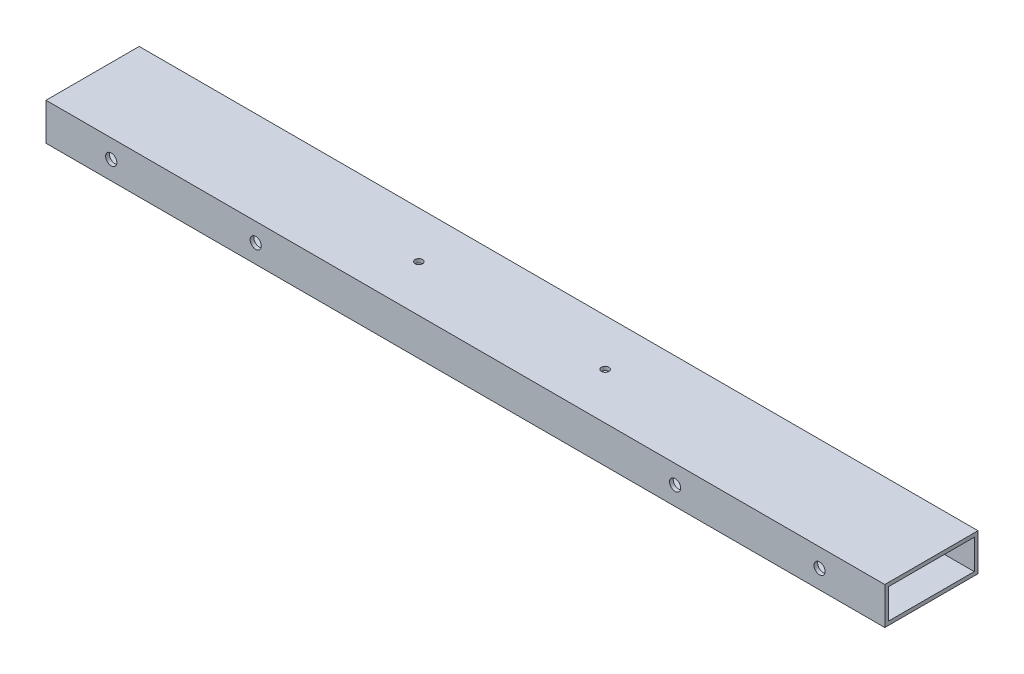
SolidWorks part; units mm, degrees
ref_plane "Спереди" through (0, 0, 0) normal (0, 0, 1) x (1, 0, 0)
ref_plane "Сверху" through (0, 0, 0) normal (0, 1, 0) x (1, 0, 0)
ref_plane "Справа" through (0, 0, 0) normal (1, 0, 0) x (0, 0, -1)
sketch "Эскиз1" plane through (0, 0, 0) normal (1, 0, 0) x (0, 0, -1)
  line L1 (-25, 10) -> (25, 10)
  line L2 (-25, 10) -> (-25, -10)
  line L3 (-25, -10) -> (25, -10)
  line L4 (25, 10) -> (25, -10)
  line L5 (-25, 10) -> (25, -10) construction
  line L6 (-25, -10) -> (25, 10) construction
  line L7 (-23, -8) -> (23, -8)
  line L8 (-23, -8) -> (-23, 8)
  line L9 (-23, 8) -> (23, 8)
  line L10 (23, -8) -> (23, 8)
  line L11 (-23, -8) -> (23, 8) construction
  line L12 (-23, 8) -> (23, -8) construction
  point P0 (0, 0)
  point P5 (0, 0)
  dimension "D1" = 46
  dimension "D2" = 16
  dimension "D3" = 50
  dimension "D4" = 20
extrude "Бобышка-Вытянуть1" add sketch "Эскиз1" along normal blind 450
sketch "Эскиз2" plane through (0, 0, -25) normal (0, 0, -1) x (-1, 0, 0)
  line L0 (-450, -10) -> (-450, 10) construction
  circle A0 centre (-415, 0) radius 3
  circle A1 centre (-337.5, 0) radius 3
  circle A2 centre (-112.5, 0) radius 3
  circle A3 centre (-35, 0) radius 3
  dimension "D1" = 6
  dimension "D2" = 35
  dimension "D3" = 35
  dimension "D4" = 77.5
  dimension "D5" = 77.5
extrude "Вырез-Вытянуть1" cut sketch "Эскиз2" against normal up to surface (50 mm away) up to face at (225, 0, 25)
sketch "Эскиз3" plane through (0, 10, 0) normal (0, 1, 0) x (1, 0, 0)
  line L0 (450, 25) -> (450, -25) construction
  circle A0 centre (175, 0) radius 2
  circle A1 centre (275, 0) radius 2
  dimension "D1" = 4
  dimension "D2" = 175
  dimension "D3" = 175
extrude "Вырез-Вытянуть2" cut sketch "Эскиз3" against normal up to surface (20 mm away) up to face at (225, -10, 0)
